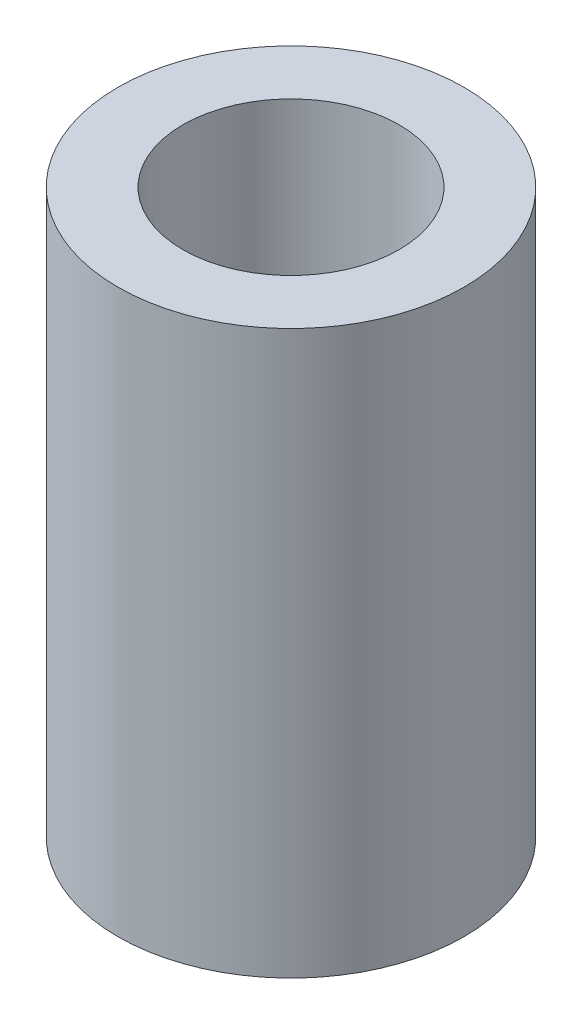
SolidWorks part; units mm, degrees
ref_plane "前视基准面" through (0, 0, 0) normal (0, 0, 1) x (1, 0, 0)
ref_plane "上视基准面" through (0, 0, 0) normal (0, 1, 0) x (1, 0, 0)
ref_plane "右视基准面" through (0, 0, 0) normal (1, 0, 0) x (0, 0, -1)
sketch "Sketch1" plane through (0, 0, 0) normal (0, 1, 0) x (1, 0, 0)
  circle A0 centre (0, 0) radius 2.5
  circle A1 centre (0, 0) radius 4
extrude "Boss-Extrude1" add sketch "Sketch1" along normal blind 13
